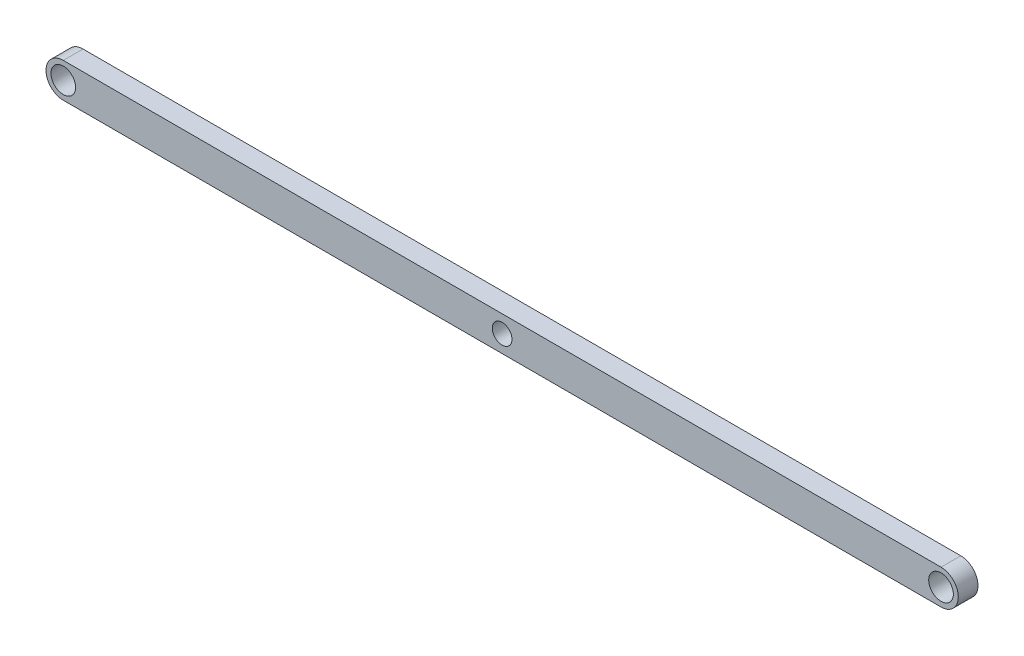
SolidWorks part; units mm, degrees
ref_plane "정면" through (0, 0, 0) normal (0, 0, 1) x (1, 0, 0)
ref_plane "윗면" through (0, 0, 0) normal (0, 1, 0) x (1, 0, 0)
ref_plane "우측면" through (0, 0, 0) normal (1, 0, 0) x (0, 0, -1)
sketch "스케치1" plane through (0, 0, 0) normal (0, 0, 1) x (1, 0, 0)
  line L0 (-92.2616, 23.2291) -> (85.7384, 23.2291)
  line L1 (-92.2616, 19.7291) -> (-92.2616, -16.1909) construction
  line L2 (85.7384, 16.2291) -> (-92.2616, 16.2291)
  line L3 (-3.2616, 23.2291) -> (-3.2616, 16.2291) construction
  line L7 (85.7384, 19.7291) -> (85.7384, -16.1909) construction
  line L11 (-95.7616, 19.7291) -> (89.2384, 19.7291) construction
  circle A0 centre (-92.2616, 19.7291) radius 2.5
  arc A1 (-92.2616, 23.2291) -> (-92.2616, 16.2291) centre (-92.2616, 19.7291) ccw
  arc A2 (85.7384, 23.2291) -> (85.7384, 16.2291) centre (85.7384, 19.7291) cw
  circle A3 centre (85.7384, 19.7291) radius 2.5
  circle A4 centre (-3.2616, 19.7291) radius 2
  point P4 (-88.6016, 16.2291)
  point P5 (89.2384, 16.2291)
  point P16 (-95.7616, 19.7291)
  point P19 (89.2384, 19.7291)
  point P25 (-92.2616, 19.7291)
  dimension "D4" = 35.92
  dimension "D1" = 4
  dimension "D3" = 3.5
  dimension "D2" = 185
  dimension "D5" = 35.92
  dimension "D6" = 3.5
  dimension "D7" = 92.5
  dimension "D8" = 3.5
extrude "보스-돌출1" add sketch "스케치1" along normal blind 4
